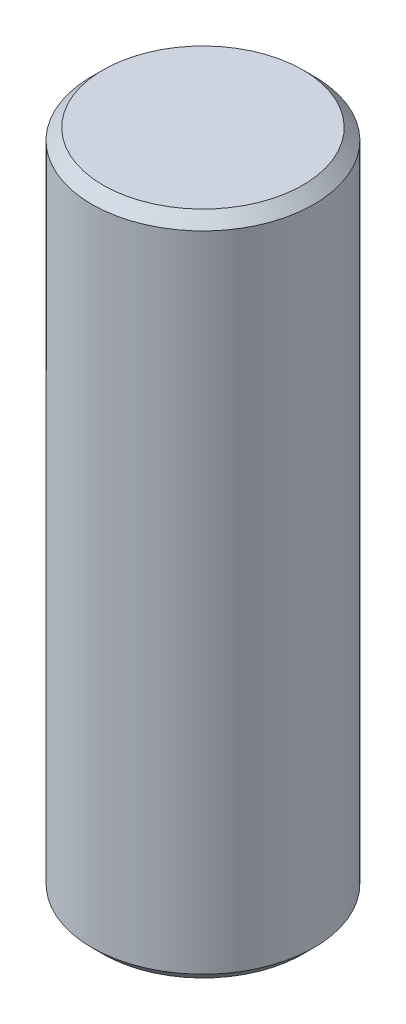
SolidWorks part; units mm, degrees
ref_plane "前视基准面" through (0, 0, 0) normal (0, 0, 1) x (1, 0, 0)
ref_plane "上视基准面" through (0, 0, 0) normal (0, 1, 0) x (1, 0, 0)
ref_plane "右视基准面" through (0, 0, 0) normal (1, 0, 0) x (0, 0, -1)
other "Configuration Table"
sketch "草图1" plane through (0, 0, 0) normal (0, 1, 0) x (1, 0, 0)
  circle A0 centre (0, 0) radius 2
  dimension "D1" = 4
extrude "凸台-拉伸1" add sketch "草图1" along normal blind 12
chamfer "倒角1" distance 0.2 angle 45 2 edges at (0, 0, 2) (0, 12, 2)
